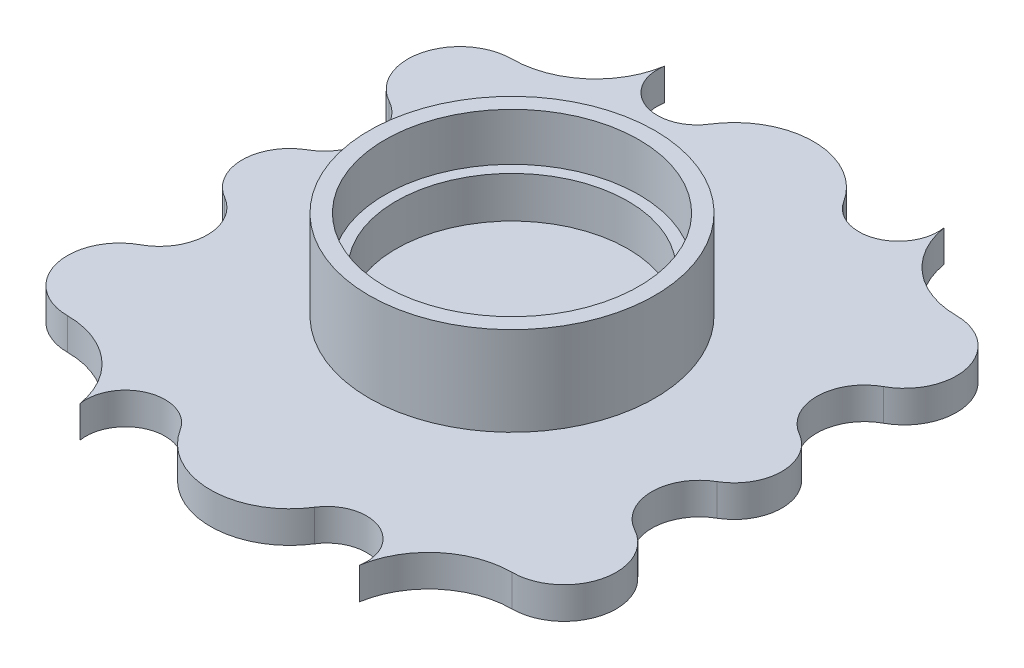
SolidWorks part; units mm, degrees
ref_plane "Alzado" through (0, 0, 0) normal (0, 0, 1) x (1, 0, 0)
ref_plane "Planta" through (0, 0, 0) normal (0, 1, 0) x (1, 0, 0)
ref_plane "Vista lateral" through (0, 0, 0) normal (1, 0, 0) x (0, 0, -1)
sketch "Croquis1" plane through (0, 0, 0) normal (0, 1, 0) x (1, 0, 0)
  line L0 (0, 138.5041) -> (0, -177.2184) construction
  line L2 (-70, -70) -> (-70, 70)
  line L4 (70, -70) -> (70, 70)
  line L5 (-70, -70) -> (70, 70) construction
  line L6 (-70, 70) -> (70, -70) construction
  line L7 (-103.4324, 0) -> (144.2109, 0) construction
  arc A1 (-21.1476, -83.3333) -> (21.1476, -83.3333) centre (0, -70) ccw
  arc A5 (-21.1476, -83.3333) -> (-44.0559, -92.0276) centre (-31.7214, -90) ccw
  arc A6 (-44.0559, -92.0276) -> (-70, -70) centre (-70, -96.2923) ccw
  arc A7 (21.1476, -83.3333) -> (44.0559, -92.0276) centre (31.7214, -90) cw
  arc A8 (44.0559, -92.0276) -> (70, -70) centre (70, -96.2923) cw
  arc A9 (44.0559, 92.0276) -> (70, 70) centre (70, 96.2923) ccw
  arc A10 (21.1476, 83.3333) -> (44.0559, 92.0276) centre (31.7214, 90) ccw
  arc A11 (-21.1476, 83.3333) -> (21.1476, 83.3333) centre (0, 70) cw
  arc A12 (-21.1476, 83.3333) -> (-44.0559, 92.0276) centre (-31.7214, 90) cw
  arc A13 (-44.0559, 92.0276) -> (-70, 70) centre (-70, 96.2923) cw
  point P0 (0, 0)
  point P14 (-25, -70)
  point P16 (-70, -70)
  dimension "D4" = 50
  dimension "D6" = 25
  dimension "D1" = 140
  dimension "D2" = 140
extrude "Saliente-Extruir1" add sketch "Croquis1" along normal blind 10
sketch "Croquis2" plane through (0, 10, 0) normal (0, 1, 0) x (1, 0, 0)
  line L0 (70, -70) -> (70, 70) construction
  line L1 (70, 70) -> (70, -70)
  line L2 (0, 152.4123) -> (0, -148.5895) construction
  line L3 (-96.3545, 0) -> (168.0513, 0) construction
  line L4 (-70, 70) -> (-70, -70)
  arc A0 (77.5, -12.9904) -> (77.5, 12.9904) centre (70, 0) ccw
  arc A1 (77.838, 39.1605) -> (77.5, 12.9904) centre (85, 25.9808) ccw
  arc A2 (77.838, 39.1605) -> (70, 70) centre (70, 53.5842) ccw
  arc A3 (77.838, -39.1605) -> (77.5, -12.9904) centre (85, -25.9808) cw
  arc A4 (77.838, -39.1605) -> (70, -70) centre (70, -53.5842) cw
  arc A5 (-77.838, -39.1605) -> (-70, -70) centre (-70, -53.5842) ccw
  arc A6 (-77.838, -39.1605) -> (-77.5, -12.9904) centre (-85, -25.9808) ccw
  arc A7 (-77.5, -12.9904) -> (-77.5, 12.9904) centre (-70, 0) cw
  arc A8 (-77.838, 39.1605) -> (-77.5, 12.9904) centre (-85, 25.9808) cw
  arc A9 (-77.838, 39.1605) -> (-70, 70) centre (-70, 53.5842) cw
  line M11 (-70, 70) -> (-70, -70)
  line M17 (70, -70) -> (70, 70)
  dimension "D1" = 30
  dimension "D2" = 30
extrude "Saliente-Extruir2" add sketch "Croquis2" against normal blind 10 contours A9 A8 M11 | A1 A2 L1 | L1 A3 A0 A1 | L4 A8 A7 A6 | A6 A5 L4 | A4 A3 M17
sketch "Croquis3" plane through (0, 10, 0) normal (0, 1, 0) x (1, 0, 0)
  circle A0 centre (0, 0) radius 40
  circle A1 centre (0, 0) radius 36.5
  dimension "D1" = 80
  dimension "D2" = 73
extrude "Saliente-Extruir3" add sketch "Croquis3" along normal blind 13
sketch "Croquis4" plane through (0, 10, 0) normal (0, 1, 0) x (1, 0, 0)
  circle A0 centre (0, 0) radius 45
  circle A1 centre (0, 0) radius 40
  circle A2 centre (0, 0) radius 40 construction
  dimension "D1" = 90
extrude "Saliente-Extruir4" add sketch "Croquis4" along normal blind 28
